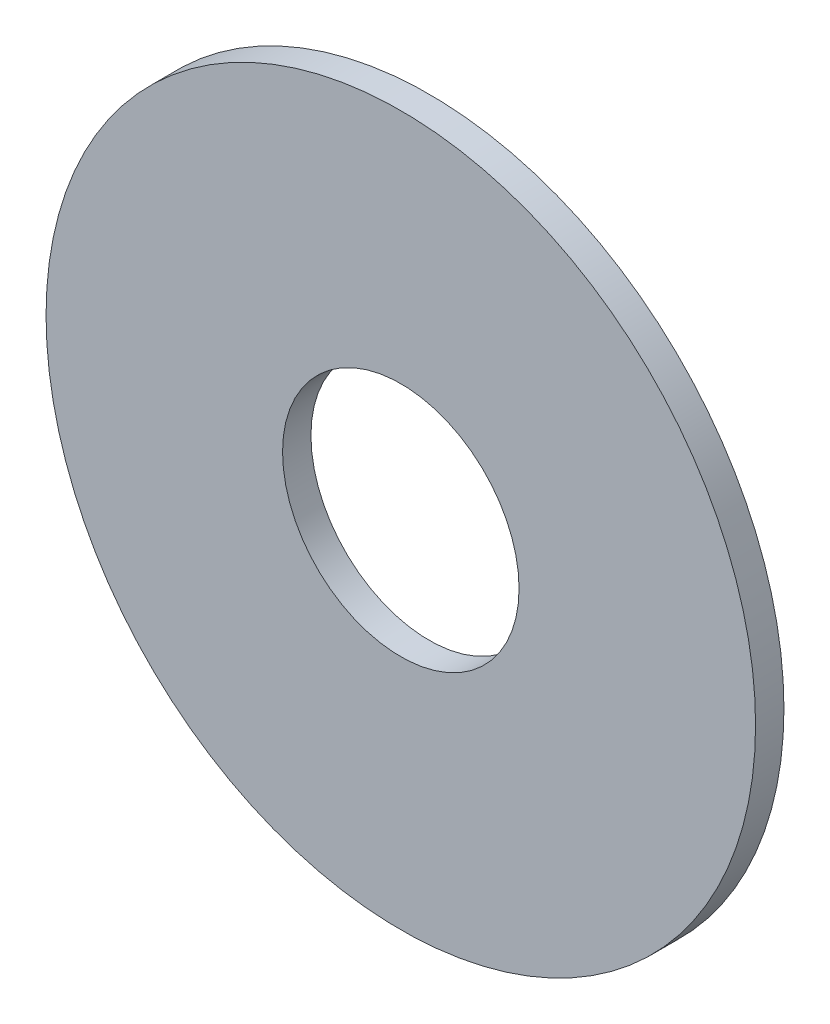
SolidWorks part; units mm, degrees
ref_plane "Front Plane" through (0, 0, 0) normal (0, 0, 1) x (1, 0, 0)
ref_plane "Top Plane" through (0, 0, 0) normal (0, 1, 0) x (1, 0, 0)
ref_plane "Right Plane" through (0, 0, 0) normal (1, 0, 0) x (0, 0, -1)
sketch "Sketch1" plane through (0, 0, 0) normal (0, 0, 1) x (1, 0, 0)
  circle A0 centre (0, 0) radius 2.5
  circle A1 centre (0, 0) radius 7.5
  dimension "D1" = 15
  dimension "D2" = 5
extrude "Boss-Extrude1" add sketch "Sketch1" along normal blind 0.6
